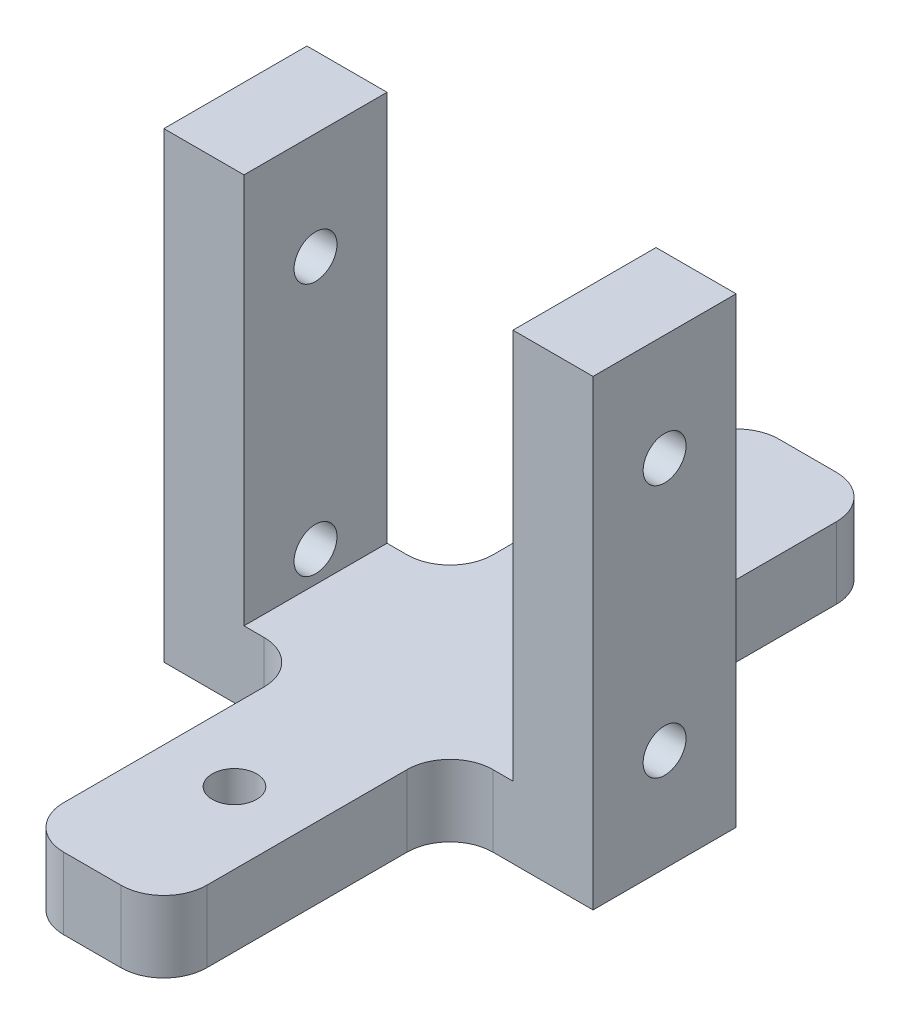
SolidWorks part; units mm, degrees
ref_plane "Front Plane" through (0, 0, 0) normal (0, 0, 1) x (1, 0, 0)
ref_plane "Top Plane" through (0, 0, 0) normal (0, 1, 0) x (1, 0, 0)
ref_plane "Right Plane" through (0, 0, 0) normal (1, 0, 0) x (0, 0, -1)
sketch "Sketch1" plane through (0, 0, 0) normal (0, 1, 0) x (1, 0, 0)
  line L1 (-31.4325, 24.8201) -> (-1.4325, 24.8201)
  line L2 (-31.4325, 24.8201) -> (-31.4325, 14.8201)
  line L3 (-31.4325, 14.8201) -> (-1.4325, 14.8201)
  line L4 (-1.4325, 24.8201) -> (-1.4325, 14.8201)
  dimension "D1" = 30
  dimension "D2" = 10
extrude "Boss-Extrude1" add sketch "Sketch1" along normal blind 5
sketch "Sketch2" plane through (0, 5, 0) normal (0, 1, 0) x (1, 0, 0)
  line L0 (-1.4325, 24.8201) -> (-31.4325, 24.8201) construction
  line L1 (-31.4325, 14.8201) -> (-25.8325, 14.8201)
  line L2 (-31.4325, 14.8201) -> (-31.4325, 24.8201)
  line L3 (-31.4325, 24.8201) -> (-25.8325, 24.8201)
  line L4 (-25.8325, 14.8201) -> (-25.8325, 24.8201)
  line L5 (-31.4325, 14.8201) -> (-1.4325, 14.8201) construction
  line L6 (-1.4325, 24.8201) -> (-7.0325, 24.8201)
  line L7 (-1.4325, 24.8201) -> (-1.4325, 14.8201)
  line L8 (-1.4325, 14.8201) -> (-7.0325, 14.8201)
  line L9 (-7.0325, 24.8201) -> (-7.0325, 14.8201)
  dimension "D1" = 18.8
extrude "Boss-Extrude2" add sketch "Sketch2" along normal blind 27.3
sketch "Sketch3" plane through (-25.8325, 0, 0) normal (1, 0, 0) x (0, 0, -1)
  line L0 (19.8201, 32.3) -> (19.8201, 5) construction
  line L1 (14.8201, 32.3) -> (24.8201, 32.3) construction
  line L2 (14.8201, 5) -> (24.8201, 5) construction
  circle A0 centre (19.8201, 7.15) radius 1.5
  circle A1 centre (19.8201, 24.85) radius 1.5
  dimension "D2" = 3
  dimension "D1" = 2.15
  dimension "D3" = 17.7
extrude "Cut-Extrude1" cut sketch "Sketch3" against normal up to surface and the other way up to surface up to face at (-31.4325, 16.15, -19.8201) other way up to face at (-1.4325, 16.15, -19.8201)
sketch "Sketch4" plane through (0, 0, -24.8201) normal (0, 0, -1) x (-1, 0, 0)
  line L0 (16.4325, 0) -> (16.4325, 5) construction
  line L1 (1.4325, 0) -> (31.4325, 0) construction
  line L2 (7.0325, 5) -> (25.8325, 5) construction
  line L4 (11.4325, 5) -> (21.4325, 5)
  line L5 (11.4325, 5) -> (11.4325, 0)
  line L6 (11.4325, 0) -> (21.4325, 0)
  line L7 (21.4325, 5) -> (21.4325, 0)
  dimension "D1" = 10
extrude "Boss-Extrude3" add sketch "Sketch4" along normal blind 20
sketch "Sketch5" plane through (0, 0, -14.8201) normal (0, 0, 1) x (1, 0, 0)
  line L0 (-16.4325, 5) -> (-16.4325, 0) construction
  line L1 (-25.8325, 5) -> (-7.0325, 5) construction
  line L2 (-31.4325, 0) -> (-1.4325, 0) construction
  line L4 (-11.4325, 5) -> (-21.4325, 5)
  line L5 (-11.4325, 5) -> (-11.4325, 0)
  line L6 (-11.4325, 0) -> (-21.4325, 0)
  line L7 (-21.4325, 5) -> (-21.4325, 0)
extrude "Boss-Extrude4" add sketch "Sketch5" along normal blind 20
sketch "Sketch6" plane through (0, 5, 0) normal (0, 1, 0) x (1, 0, 0)
  line L0 (-16.4325, 44.8201) -> (-16.4325, -5.1799) construction
  line L1 (-21.4325, 44.8201) -> (-11.4325, 44.8201) construction
  line L2 (-11.4325, -5.1799) -> (-21.4325, -5.1799) construction
  line L3 (-31.4325, 19.8201) -> (-1.4325, 19.8201) construction
  line L4 (-31.4325, 24.8201) -> (-31.4325, 14.8201) construction
  line L5 (-1.4325, 14.8201) -> (-1.4325, 24.8201) construction
  circle A0 centre (-16.4325, 34.8857) radius 1.55
  circle A1 centre (-16.4325, 4.7546) radius 1.55
  point P16 (0, 0)
  dimension "D1" = 3.1
  dimension "D2" = 30.1312
extrude "Cut-Extrude2" cut sketch "Sketch6" against normal through all
fillet "Fillet1" radius 3 8 edges at (-21.4325, 2.5, -44.8201) (-11.4325, 2.5, -44.8201) (-11.4325, 2.5, 5.1799) (-21.4325, 2.5, 5.1799)
